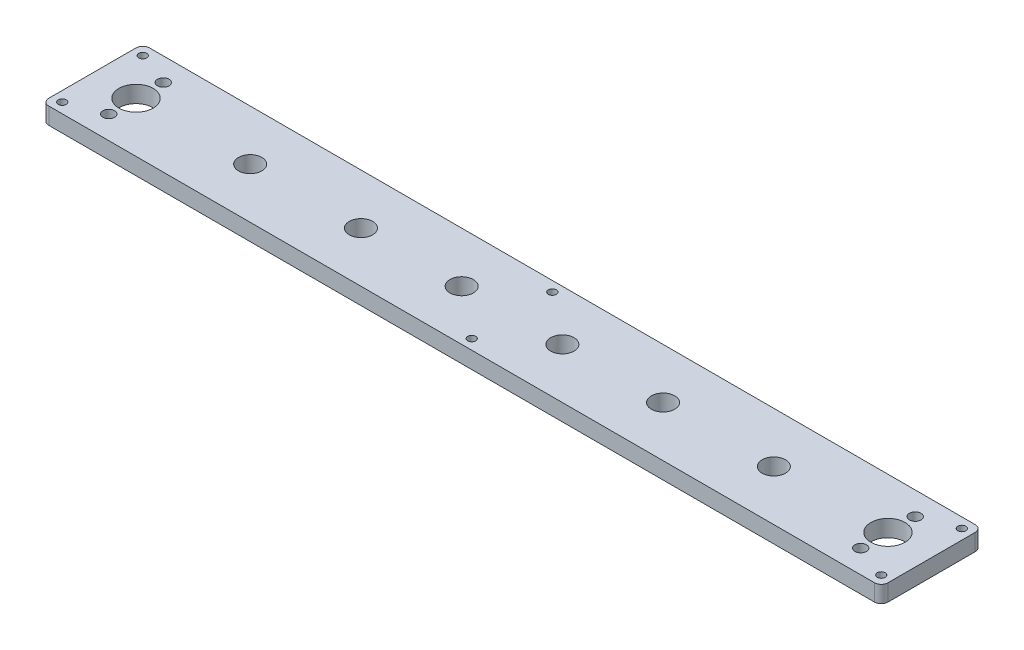
SolidWorks part; units mm, degrees
material "Acrylic (Medium-high impact)"
ref_plane "Front Plane" through (0, 0, 0) normal (0, 0, 1) x (1, 0, 0)
ref_plane "Top Plane" through (0, 0, 0) normal (0, 1, 0) x (1, 0, 0)
ref_plane "Right Plane" through (0, 0, 0) normal (1, 0, 0) x (0, 0, -1)
sketch "Sketch1" plane through (0, 0, 0) normal (0, 1, 0) x (1, 0, 0)
  line L1 (-158.75, -19.05) -> (158.75, -19.05)
  line L2 (-158.75, -19.05) -> (-158.75, 19.05)
  line L3 (-158.75, 19.05) -> (158.75, 19.05)
  line L4 (158.75, -19.05) -> (158.75, 19.05)
  line L5 (-158.75, -19.05) -> (158.75, 19.05) construction
  line L6 (-158.75, 19.05) -> (158.75, -19.05) construction
  point P0 (0, 0)
  dimension "D1" = 317.5
  dimension "D2" = 38.1
extrude "Boss-Extrude1" add sketch "Sketch1" along normal mid plane 6.35
sketch "Sketch2" plane through (0, 3.175, 0) normal (0, 1, 0) x (1, 0, 0)
  line L0 (-133.35, 0) -> (0, 0) construction
  line L1 (-142.24, -10.3187) -> (-142.24, 10.3187) construction
  line L2 (-158.75, 19.05) -> (-158.75, -19.05) construction
  line L4 (142.24, -10.3187) -> (142.24, 10.3187) construction
  line L5 (158.75, -19.05) -> (158.75, 19.05) construction
  circle A0 centre (-142.24, 0) radius 10.16 construction
  circle A1 centre (-99.06, 0) radius 4.4196
  circle A2 centre (-57.15, 0) radius 4.4196
  circle A3 centre (-19.05, 0) radius 4.4196
  circle A4 centre (19.05, 0) radius 4.4196
  circle A5 centre (57.15, 0) radius 4.4196
  circle A6 centre (142.24, 0) radius 10.16 construction
  circle A7 centre (-142.24, 0) radius 6.477
  circle A8 centre (-142.24, -10.3187) radius 2.1908
  circle A9 centre (-142.24, 10.3187) radius 2.1908
  circle A10 centre (142.24, 0) radius 6.477
  circle A11 centre (142.24, -10.3187) radius 2.1908
  circle A12 centre (142.24, 10.3187) radius 2.1908
  circle A13 centre (99.06, 0) radius 4.4196
  point P3 (-158.75, 0)
  point P28 (-142.24, -8.128)
  point P29 (-142.24, 8.128)
  point P30 (-142.24, 0)
  point P37 (142.24, -8.128)
  point P38 (142.24, 8.128)
  point P39 (142.24, 0)
  dimension "D1" = 20.32
  dimension "D5" = 8.8392
  dimension "D9" = 12.954
  dimension "D10" = 4.3815
  dimension "D12" = 12.954
  dimension "D13" = 4.3815
  dimension "D2" = 43.18
  dimension "D3" = 16.51
  dimension "D4" = 38.1
  dimension "D6" = 43.18
  dimension "D7" = 38.1
  dimension "D8" = 38.1
  dimension "D11" = 10.3187
  dimension "D14" = 10.3187
  dimension "D15" = 19.05
  dimension "D16" = 16.51
extrude "Cut-Extrude1" cut sketch "Sketch2" against normal through all
sketch "Sketch3" plane through (0, 3.175, 0) normal (0, 1, 0) x (1, 0, 0)
  line L0 (-158.75, 19.05) -> (-158.75, -19.05) construction
  line L1 (154.94, -15.24) -> (-154.94, -15.24) construction
  line L2 (154.94, -15.24) -> (154.94, 15.24) construction
  line L3 (154.94, 15.24) -> (-154.94, 15.24) construction
  line L4 (-154.94, -15.24) -> (-154.94, 15.24) construction
  line L5 (154.94, -15.24) -> (-154.94, 15.24) construction
  line L6 (154.94, 15.24) -> (-154.94, -15.24) construction
  line L7 (158.75, 19.05) -> (-158.75, 19.05) construction
  circle A0 centre (-154.94, 15.24) radius 1.5113
  circle A1 centre (-154.94, -15.24) radius 1.5113
  circle A2 centre (154.94, -15.24) radius 1.5113
  circle A3 centre (154.94, 15.24) radius 1.5113
  circle A4 centre (0, 15.24) radius 1.5113
  circle A5 centre (0, -15.24) radius 1.5113
  point P0 (0, 0)
  dimension "D1" = 3.0226
  dimension "D2" = 3.81
  dimension "D3" = 3.81
extrude "Cut-Extrude2" cut sketch "Sketch3" against normal through all
fillet "Fillet1" radius 2.54 4 edges at (158.75, 0, 19.05) (-158.75, 0, 19.05) (158.75, 0, -19.05) (-158.75, 0, -19.05)
sketch "Sketch4" [suppressed] plane through (0, 4.7625, 0) normal (0, 1, 0) x (1, 0, 0)
  circle A0 centre (99.06, 0) radius 8.7313
  circle A1 centre (-99.06, 0) radius 8.7313
  circle A2 centre (-57.15, 0) radius 8.7313
  circle A3 centre (-19.05, 0) radius 8.7313
  circle A4 centre (19.05, 0) radius 8.7312
  circle A5 centre (57.15, 0) radius 8.7313
  dimension "D2" = 17.4625
extrude "Cut-Extrude3" [suppressed] cut sketch "Sketch4" against normal through all
